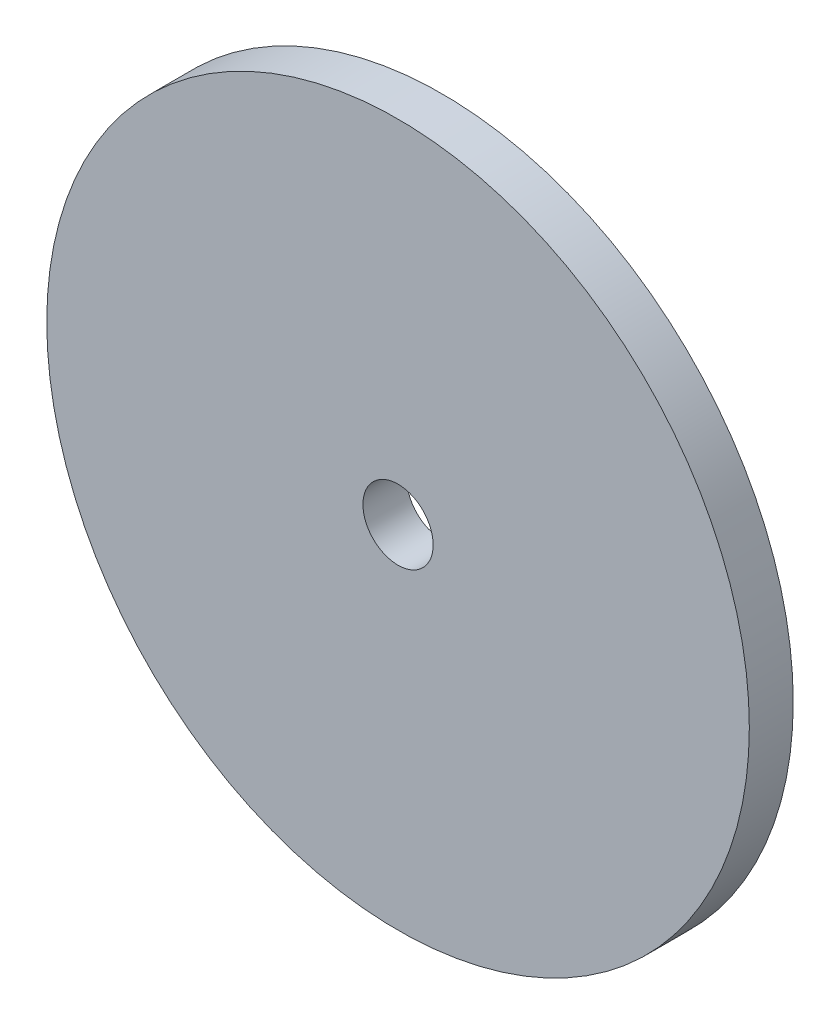
SolidWorks part; units mm, degrees
material "Maple"
ref_plane "前视基准面" through (0, 0, 0) normal (0, 0, 1) x (1, 0, 0)
ref_plane "上视基准面" through (0, 0, 0) normal (0, 1, 0) x (1, 0, 0)
ref_plane "右视基准面" through (0, 0, 0) normal (1, 0, 0) x (0, 0, -1)
sketch "草图1" plane through (0, 0, 0) normal (0, 0, 1) x (1, 0, 0)
  circle A0 centre (0, 0) radius 4
  circle A1 centre (0, 0) radius 40
extrude "凸台-拉伸1" add sketch "草图1" along normal blind 5
